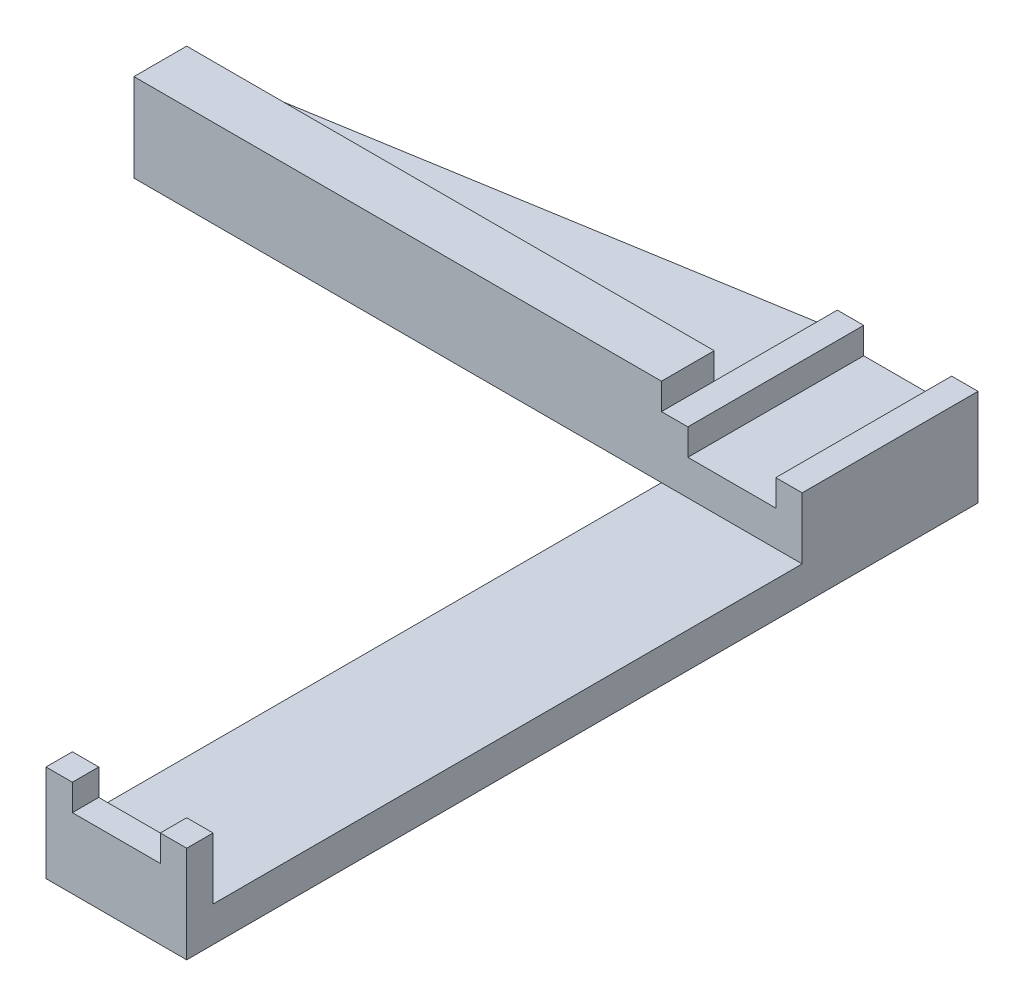
SolidWorks part; units mm, degrees
ref_plane "Front Plane" through (0, 0, 0) normal (0, 0, 1) x (1, 0, 0)
ref_plane "Top Plane" through (0, 0, 0) normal (0, 1, 0) x (1, 0, 0)
ref_plane "Right Plane" through (0, 0, 0) normal (1, 0, 0) x (0, 0, -1)
sketch "Sketch1" plane through (0, 0, 0) normal (0, 1, 0) x (1, 0, 0)
  line L0 (0, 0) -> (30, 0)
  line L1 (30, 0) -> (30, -35)
  line L2 (30, -35) -> (38, -35)
  line L3 (38, -35) -> (38, 10)
  line L4 (38, 10) -> (30, 10)
  line L5 (30, 10) -> (0, 5)
  line L6 (0, 5) -> (0, 0)
  point P6 (0, 2.5)
  dimension "D1" = 8
  dimension "D2" = 45
  dimension "D3" = 30
  dimension "D4" = 5
  dimension "D5" = 10
extrude "Boss-Extrude1" add sketch "Sketch1" along normal blind 12
sketch "Sketch2" plane through (0, 12, 0) normal (0, 1, 0) x (1, 0, 0)
  line L0 (0, 0) -> (30, 0) construction
  line L1 (30, 0) -> (38, 0)
  line L2 (30, 0) -> (30, -33.5)
  line L3 (30, -33.5) -> (38, -33.5)
  line L4 (38, 0) -> (38, -33.5)
  line L5 (30, 0) -> (30, -35) construction
  line L6 (38, -35) -> (38, 10) construction
  line L7 (30, -35) -> (38, -35) construction
  dimension "D1" = 1.5
extrude "Cut-Extrude1" cut sketch "Sketch2" against normal blind 10
sketch "Sketch3" plane through (0, 12, 0) normal (0, 1, 0) x (1, 0, 0)
  line L1 (30, 10) -> (38, 10)
  line L2 (30, 10) -> (30, -35)
  line L3 (30, -35) -> (38, -35)
  line L4 (38, 10) -> (38, -35)
extrude "Cut-Extrude2" cut sketch "Sketch3" against normal blind 6.5
sketch "Sketch4" plane through (0, 5.5, 0) normal (0, 1, 0) x (1, 0, 0)
  line L0 (38, 10) -> (30, 10) construction
  line L1 (31.5, 10) -> (36.5, 10)
  line L2 (31.5, 10) -> (31.5, 0)
  line L3 (31.5, 0) -> (36.5, 0)
  line L4 (36.5, 10) -> (36.5, 0)
  line L5 (38, 0) -> (30, 0) construction
  line L6 (38, 0) -> (38, 10) construction
  dimension "D1" = 5
  dimension "D2" = 1.5
extrude "Cut-Extrude3" cut sketch "Sketch4" against normal blind 1.5
sketch "Sketch5" plane through (0, 5.5, 0) normal (0, 1, 0) x (1, 0, 0)
  line L0 (38, -33.5) -> (30, -33.5) construction
  line L1 (31.5, -33.5) -> (36.5, -33.5)
  line L2 (31.5, -33.5) -> (31.5, -35)
  line L3 (31.5, -35) -> (36.5, -35)
  line L4 (36.5, -33.5) -> (36.5, -35)
  line L5 (30, -35) -> (38, -35) construction
  line L6 (30, -33.5) -> (30, -35) construction
  dimension "D1" = 5
  dimension "D2" = 1.5
extrude "Cut-Extrude4" cut sketch "Sketch5" against normal blind 1.5
sketch "Sketch6" plane through (0, 0, 0) normal (0, -1, 0) x (1, 0, 0)
  line L0 (0, 0) -> (30, 0)
  line L1 (30, 0) -> (30, -10)
  line L2 (30, -10) -> (0, -5)
  line L3 (0, -5) -> (0, 0)
extrude "Cut-Extrude5" cut sketch "Sketch6" against normal blind 2
sketch "Sketch7" plane through (0, 12, 0) normal (0, 1, 0) x (1, 0, 0)
  line L0 (0, 5) -> (30, 10)
  line L1 (30, 10) -> (0, 5) construction
  line L2 (30, 10) -> (30, 0)
  line L3 (30, 0) -> (0, 0)
  line L4 (0, 0) -> (0, 5)
extrude "Cut-Extrude7" cut sketch "Sketch7" against normal blind 1
sketch "Sketch9" plane through (0, 11, 0) normal (0, 1, 0) x (1, 0, 0)
  line L0 (0, 5) -> (30, 10)
  line L1 (30, 10) -> (30, 3)
  line L2 (30, 10) -> (30, 0) construction
  line L3 (30, 3) -> (0, 3)
  line L4 (0, 5) -> (0, 0) construction
  line L5 (0, 3) -> (0, 5)
  line L6 (0, 0) -> (30, 0) construction
  dimension "D1" = 3
extrude "Cut-Extrude8" cut sketch "Sketch9" against normal blind 4
sketch "Sketch10" plane through (0, 11, 0) normal (0, 1, 0) x (1, 0, 0)
  line L1 (0, 3) -> (30, 3)
  line L2 (0, 3) -> (0, 0)
  line L3 (0, 0) -> (30, 0)
  line L4 (30, 3) -> (30, 0)
extrude "Cut-Extrude9" cut sketch "Sketch10" against normal blind 4
sketch "Sketch11" plane through (0, 7, 0) normal (0, 1, 0) x (1, 0, 0)
  line L0 (0, 5) -> (30, 10)
  line L1 (30, 10) -> (0, 5) construction
  line L2 (30, 10) -> (30, 3)
  line L3 (30, 10) -> (30, 0) construction
  line L4 (30, 3) -> (0, 3)
  line L5 (0, 3) -> (0, 5)
  line L6 (0, 0) -> (30, 0) construction
  dimension "D1" = 3
extrude "Cut-Extrude10" cut sketch "Sketch11" against normal blind 2.5
sketch "Sketch13" plane through (0, 4.5, 0) normal (0, 1, 0) x (1, 0, 0)
  line L0 (30, 3) -> (30, 10) construction
  line L1 (30, 5.5) -> (38, 5.5)
  line L2 (30, 5.5) -> (30, 0)
  line L3 (30, 0) -> (38, 0)
  line L4 (38, 5.5) -> (38, 0)
  point P7 (42.4823, -0.7389)
  dimension "D1" = 5.5
